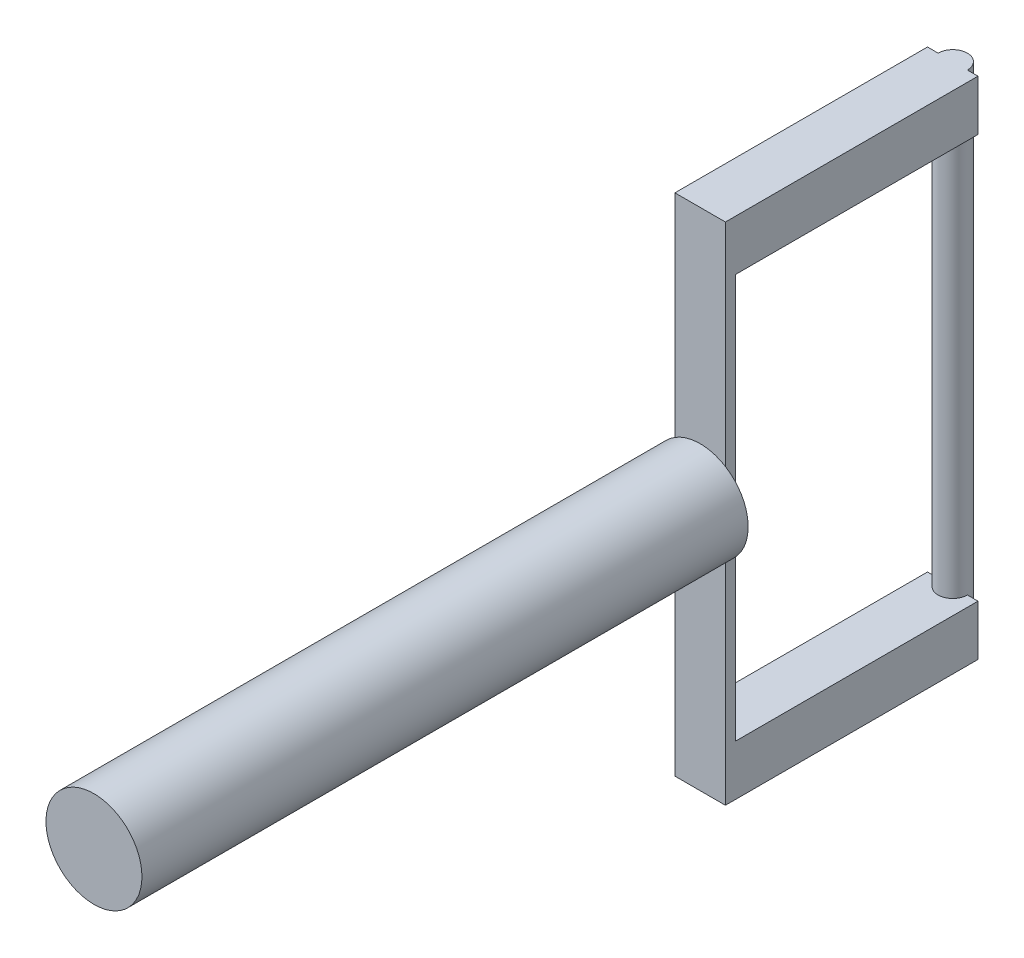
SolidWorks part; units mm, degrees
ref_plane "前视基准面" through (0, 0, 0) normal (0, 0, 1) x (1, 0, 0)
ref_plane "上视基准面" through (0, 0, 0) normal (0, 1, 0) x (1, 0, 0)
ref_plane "右视基准面" through (0, 0, 0) normal (1, 0, 0) x (0, 0, -1)
sketch "草图1" plane through (0, 0, 0) normal (0, 1, 0) x (1, 0, 0)
  circle A0 centre (0, 0) radius 0.29
  dimension "D1" = 0.58
extrude "凸台-拉伸1" add sketch "草图1" along normal mid plane 10 contours A0
sketch "草图2" plane through (0, 0, 0) normal (0, 0, 1) x (1, 0, 0)
  line L1 (-0.5, 5) -> (0.5, 5)
  line L2 (-0.5, 5) -> (-0.5, 4)
  line L3 (-0.5, 4) -> (0.5, 4)
  line L4 (0.5, 5) -> (0.5, 4)
  line L5 (-0.5, 5) -> (0.5, 4) construction
  line L6 (-0.5, 4) -> (0.5, 5) construction
  line L7 (0.5, -4) -> (-0.5, -4)
  line L8 (0.5, -4) -> (0.5, -5)
  line L9 (0.5, -5) -> (-0.5, -5)
  line L10 (-0.5, -4) -> (-0.5, -5)
  line L11 (0.5, -4) -> (-0.5, -5) construction
  line L12 (0.5, -5) -> (-0.5, -4) construction
  point P0 (0, 4.5)
  point P5 (0, -4.5)
  dimension "D1" = 4.5
  dimension "D2" = 4.5
extrude "凸台-拉伸2" add sketch "草图2" along normal blind 5
sketch "草图3" plane through (0, 0, 5) normal (0, 0, 1) x (1, 0, 0)
  line L1 (-0.5, 4) -> (0.5, 4)
  line L2 (-0.5, 4) -> (-0.5, -4)
  line L3 (-0.5, -4) -> (0.5, -4)
  line L4 (0.5, 4) -> (0.5, -4)
  line L5 (-0.5, 4) -> (0.5, -4) construction
  line L6 (-0.5, -4) -> (0.5, 4) construction
  point P0 (0, 0)
  dimension "D1" = 1
  dimension "D2" = 8
extrude "凸台-拉伸3" add sketch "草图3" against normal blind 0.2
sketch "草图4" plane through (0, 0, 5) normal (0, 0, 1) x (1, 0, 0)
  circle A0 centre (0, 0) radius 0.95
  dimension "D1" = 1.9
extrude "凸台-拉伸4" add sketch "草图4" along normal blind 12
